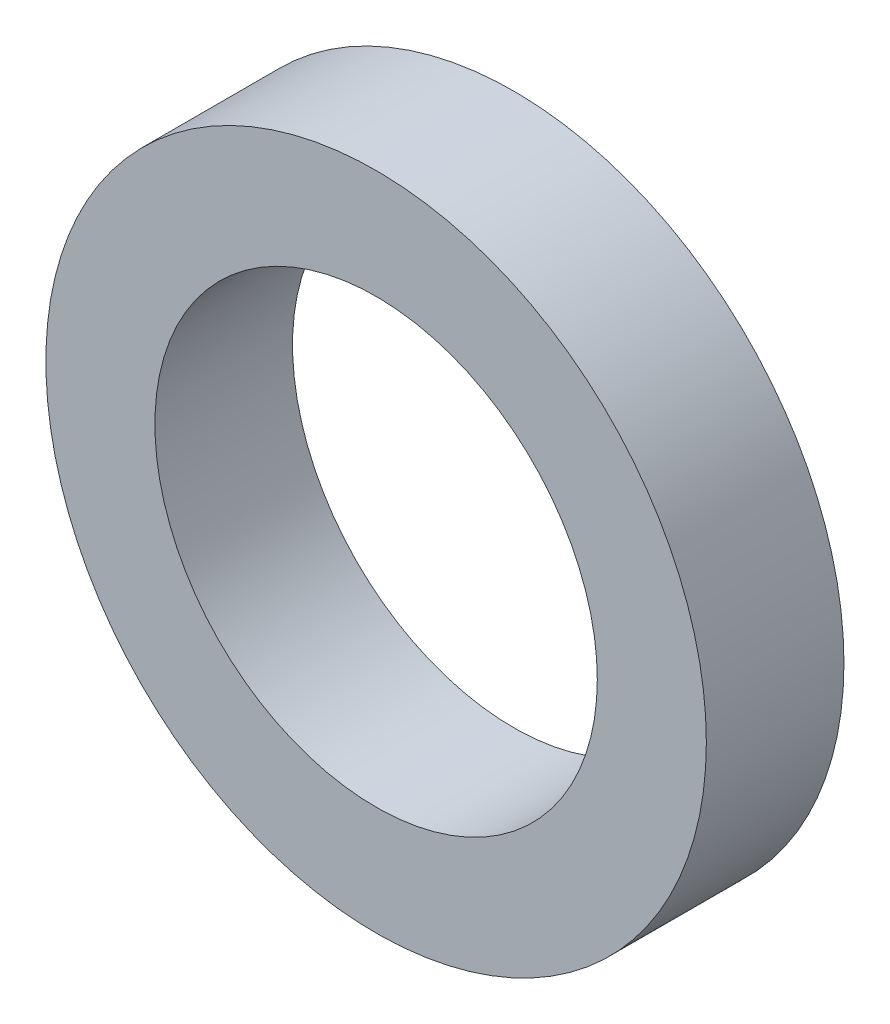
SolidWorks part; units mm, degrees
material "EPDM"
ref_plane "Front Plane" through (0, 0, 0) normal (0, 0, 1) x (1, 0, 0)
ref_plane "Top Plane" through (0, 0, 0) normal (0, 1, 0) x (1, 0, 0)
ref_plane "Right Plane" through (0, 0, 0) normal (1, 0, 0) x (0, 0, -1)
sketch "Extrude sketch 1" plane through (0, 0, 0) normal (0, 0, 1) x (1, 0, 0)
  circle A0 centre (0, 0) radius 48
  circle A1 centre (0, 0) radius 32.15
  dimension "D1" = 64.3
  dimension "D2" = 96
extrude "Extrude 1" add sketch "Extrude sketch 1" along normal blind 20 separate body
